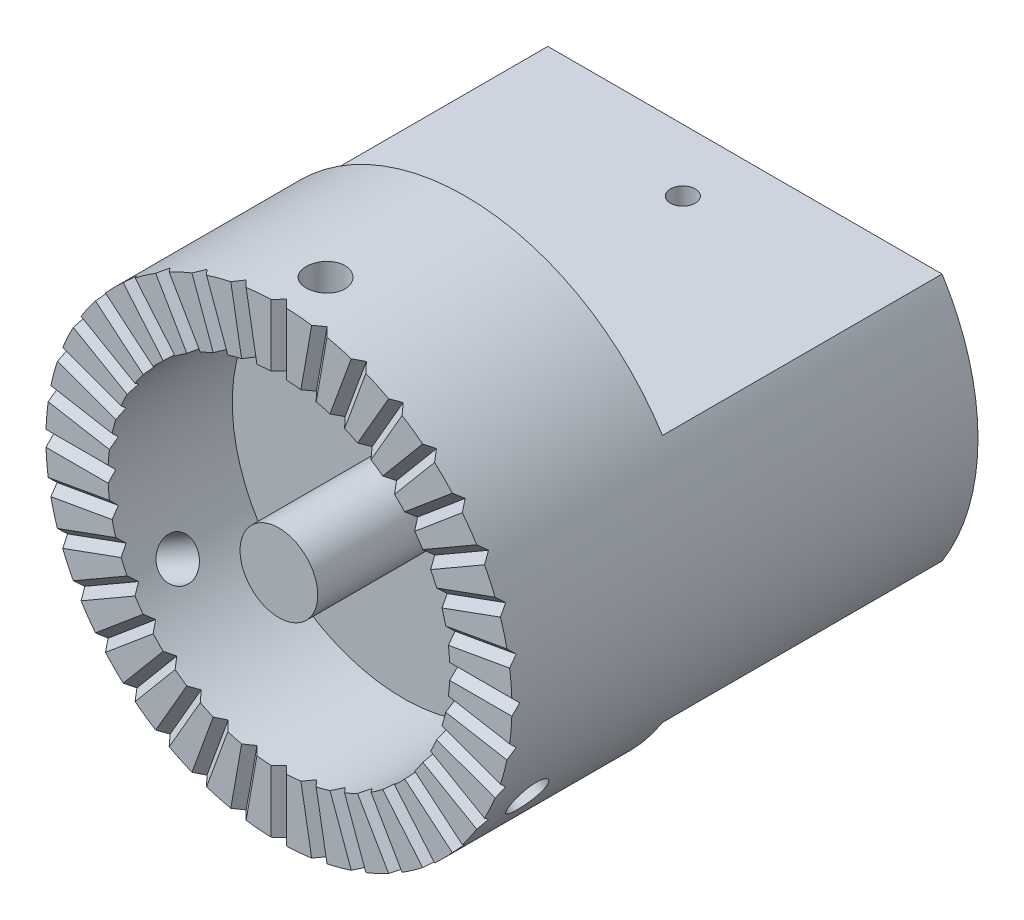
SolidWorks part; units mm, degrees
ref_plane "Front Plane" through (0, 0, 0) normal (0, 0, 1) x (1, 0, 0)
ref_plane "Top Plane" through (0, 0, 0) normal (0, 1, 0) x (1, 0, 0)
ref_plane "Right Plane" through (0, 0, 0) normal (1, 0, 0) x (0, 0, -1)
sketch "Sketch2" plane through (0, 0, 0) normal (0, 0, 1) x (1, 0, 0)
  circle A0 centre (0, 0) radius 15
  dimension "D1" = 30
extrude "Core" add sketch "Sketch2" along normal blind 30
sketch "Sketch4" plane through (0, 0, 0) normal (0, 0, -1) x (-1, 0, 0)
  line L1 (-12.6886, 33.9479) -> (12.6886, 33.9479)
  line L2 (-12.6886, 33.9479) -> (-12.6886, 8)
  line L3 (-12.6886, 8) -> (12.6886, 8)
  line L4 (12.6886, 33.9479) -> (12.6886, 8)
  circle A0 centre (0, 0) radius 15 construction
  point P4 (-10.2054, 10.9931)
  point P5 (-12.6886, 33.9479)
  dimension "D1" = 8
extrude "Flat" cut sketch "Sketch4" against normal blind 18
ref_plane "Plane2" through (0, 0, 0) normal (0, 1, 0) x (1, 0, 0)
mirror "Mirror2" about plane through (0, 0, 0) normal (0, 1, 0) of "Flat"
sketch "Sketch7" plane through (0, 8, 0) normal (0, 1, 0) x (1, 0, 0)
  line L0 (0, -1005.8427) -> (0, 48994.1573) construction
  line L2 (12.6886, 0) -> (-12.6886, 0) construction
  circle A0 centre (0, -4) radius 1.2
  point P6 (0, 0)
  dimension "D1" = 2.4
  dimension "D2" = 4
extrude "Cut-Extrude3" [suppressed] cut sketch "Sketch7" against normal through all
pattern_linear "LPattern2" [suppressed] count 2 spacing 10
sketch "Sketch9" plane through (0, 0, 30) normal (0, 0, 1) x (1, 0, 0)
  circle A0 centre (0, 0) radius 11
  circle A1 centre (0, 0) radius 15 construction
  dimension "D1" = 22
extrude "Cut-Extrude4" cut sketch "Sketch9" against normal blind 8
hole_wizard "M6x1.0 Tapped Hole7" [suppressed] positions "Sketch26" profile "Sketch27" tap size "M6x1.0" standard "BSI"
sketch "Sketch26" plane through (0, 0, 22) normal (0, 0, 1) x (1, 0, 0)
  point P0 (0, 0)
sketch "Sketch27" plane through (0, 0, 22) normal (1, 0, 0) x (0, -1, 0)
  line L0 (0, 0) -> (0, 6.5022)
  line L1 (0, 6.5022) -> (2.5, 5)
  line L2 (2.5, 5) -> (2.5, 0)
  line L5 (2.5, 0) -> (0, 0)
  line L10 (0, 6.5022) -> (-2.5, 5) construction
  line L11 (0, -6.35) -> (0, 107.95) construction
  dimension "Tap Drill Dia." = 5
  dimension "Tap Drill Depth" = 5
  dimension "Drill Angle" = 118
cosmetic thread "Hole Thread7" [suppressed] parameters "D1"=5, "D2"=6
sketch "Sketch29" plane through (0, 0, 0) normal (0, 1, 0) x (1, 0, 0)
  line L0 (0, -29.5) -> (0, -33.0503) construction
  line L1 (-11, -30) -> (11, -30) construction
  line L2 (-0.5, -30) -> (0.5, -30)
  line L3 (-0.5, -30) -> (0, -29.5)
  line L4 (0, -29.5) -> (0.5, -30)
  dimension "D1" = 0.5
  dimension "D2" = 90
extrude "Cut-Extrude5" cut sketch "Sketch29" against normal through all
ref_axis "Axis1" through (0, 0, 30) along (0, 0, -1)
pattern_circular "CirPattern2" count 36 over 360 about axis through (0, 0, 0) along (0, 0, 1) of "Cut-Extrude5"
hole_wizard "M3x0.5 Tapped Hole2" positions "3DSketch2" profile "Sketch31" tap size "M3x0.5" standard "BSI"
sketch3d "3DSketch2"
  point P0 (0, 15, 27)
  dimension "D1" = 3
sketch "Sketch31" plane through (0, 15, 27) normal (1, 0, 0) x (0, 0, 1)
  line L0 (0, 0) -> (0, 30)
  line L1 (0, 30) -> (1.25, 30)
  line L2 (1.25, 30) -> (1.25, 0)
  line L5 (1.25, 0) -> (0, 0)
  line L11 (0, -6.35) -> (0, 107.95) construction
  dimension "Thru Tap Drill Dia." = 2.5
  dimension "Thru Tap Drill Depth" = 30
cosmetic thread "Hole Thread9" parameters "D2"=3
pattern_circular "CirPattern3" count 3 over 360 about axis through (0, 0, 30) along (0, 0, -1) of "M3x0.5 Tapped Hole2"
cosmetic thread "Hole Thread10" parameters "D2"=3
cosmetic thread "Hole Thread11" parameters "D2"=3
sketch "Sketch32" plane through (0, 0, 22) normal (0, 0, 1) x (1, 0, 0)
  circle A0 centre (0, 0) radius 2.5
  dimension "D1" = 5
extrude "Boss-Extrude1" add sketch "Sketch32" along normal blind 8
hole_wizard "M2x0.4 Tapped Hole2" positions "Sketch35" profile "Sketch36" tap size "M2x0.4" standard "BSI" end condition up to next
sketch "Sketch35" plane through (0, -8, 0) normal (0, -1, 0) x (-1, 0, 0)
  line L0 (-12.6886, 0) -> (12.6886, 0) construction
  point P0 (0, -4)
  dimension "D1" = 4
sketch "Sketch36" plane through (0, -8, 4) normal (1, 0, 0) x (0, 0, -1)
  line L0 (0, 0) -> (0, 16.001)
  line L1 (0, 16.001) -> (0.8, 16.001)
  line L2 (0.8, 16.001) -> (0.8, 0)
  line L5 (0.8, 0) -> (0, 0)
  line L11 (0, -6.35) -> (0, 107.95) construction
  dimension "Thru Tap Drill Dia." = 1.6
  dimension "Thru Tap Drill Depth" = 16.001
cosmetic thread "Hole Thread14" parameters "D2"=2
pattern_linear "LPattern3" count 2 spacing 10 along (0, 0, 1) of "M2x0.4 Tapped Hole2"
cosmetic thread "Hole Thread15" parameters "D2"=2
